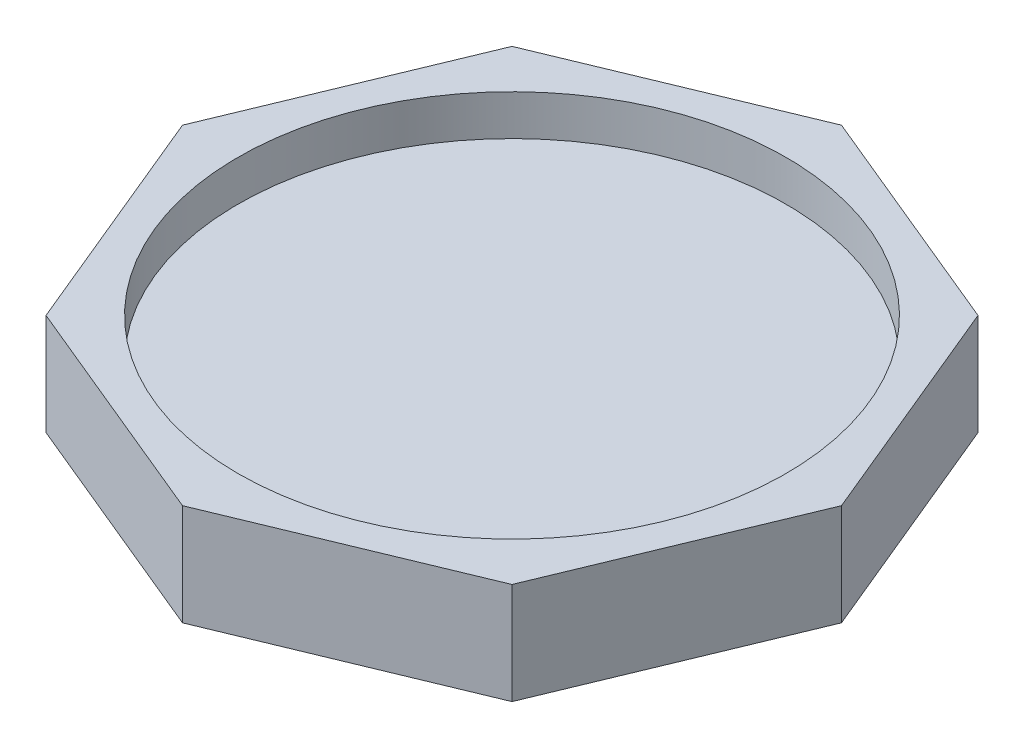
SolidWorks part; units mm, degrees
ref_plane "Front Plane" through (0, 0, 0) normal (0, 0, 1) x (1, 0, 0)
ref_plane "Top Plane" through (0, 0, 0) normal (0, 1, 0) x (1, 0, 0)
ref_plane "Right Plane" through (0, 0, 0) normal (1, 0, 0) x (0, 0, -1)
sketch "Sketch1" plane through (0, 0, 0) normal (0, 1, 0) x (1, 0, 0)
  line L7 (162.3588, 0) -> (114.805, 114.805)
  line L8 (114.805, 114.805) -> (0, 162.3588)
  line L9 (0, 162.3588) -> (-114.805, 114.805)
  line L10 (-114.805, 114.805) -> (-162.3588, 0)
  line L11 (-162.3588, 0) -> (-114.805, -114.805)
  line L12 (-114.805, -114.805) -> (0, -162.3588)
  line L13 (0, -162.3588) -> (114.805, -114.805)
  line L14 (114.805, -114.805) -> (162.3588, 0)
  circle A0 centre (0, 0) radius 150 construction
  dimension "D1" = 300
extrude "Boss-Extrude1" add sketch "Sketch1" along normal blind 50
sketch "Sketch2" plane through (0, 50, 0) normal (0, 1, 0) x (1, 0, 0)
  line L32 (114.805, -114.805) -> (162.3588, 0)
  line L33 (162.3588, 0) -> (114.805, 114.805)
  line L34 (114.805, 114.805) -> (0, 162.3588)
  line L35 (0, 162.3588) -> (-114.805, 114.805)
  line L36 (-114.805, 114.805) -> (-162.3588, 0)
  line L37 (-162.3588, 0) -> (-114.805, -114.805)
  line L38 (-114.805, -114.805) -> (0, -162.3588)
  line L39 (0, -162.3588) -> (114.805, -114.805)
  line L40 (114.805, -114.805) -> (162.3588, 0)
  line L41 (162.3588, 0) -> (114.805, 114.805)
  line L42 (114.805, 114.805) -> (0, 162.3588)
  line L43 (0, 162.3588) -> (-114.805, 114.805)
  line L44 (-114.805, 114.805) -> (-162.3588, 0)
  line L45 (-162.3588, 0) -> (-114.805, -114.805)
  line L46 (-114.805, -114.805) -> (0, -162.3588)
  line L47 (0, -162.3588) -> (114.805, -114.805)
  circle A0 centre (0, 0) radius 135
  dimension "D1" = 270
  dimension "D2" = 0
extrude "Cut-Extrude1" cut sketch "Sketch2" against normal blind 20 contours A0
